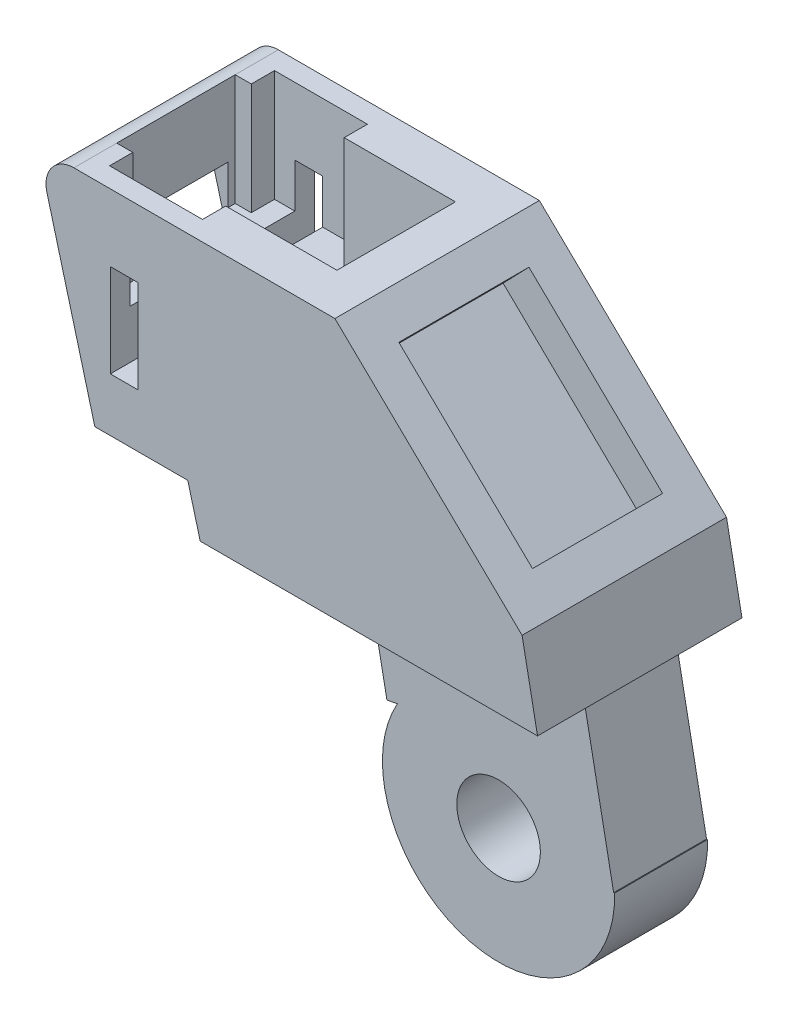
SolidWorks part; units mm, degrees
ref_plane "Front Plane" through (0, 0, 0) normal (0, 0, 1) x (1, 0, 0)
ref_plane "Top Plane" through (0, 0, 0) normal (0, 1, 0) x (1, 0, 0)
ref_plane "Right Plane" through (0, 0, 0) normal (1, 0, 0) x (0, 0, -1)
sketch "Sketch1" plane through (0, 0, 0) normal (0, 0, 1) x (1, 0, 0)
  line L0 (-2.3592, -1.1297) -> (-2.3592, 7.8703) construction
  line L1 (-14.5206, 6.2601) -> (9.8021, 0.4806) construction
  circle A0 centre (-2.3592, 3.3703) radius 4.5
  circle A1 centre (-2.3592, 3.3703) radius 12.5
  point P7 (-2.3592, 3.3703)
extrude "Boss-Extrude1" add sketch "Sketch1" along normal blind 10
ref_plane "Plane1" through (0, 0, 5) normal (0, 0, 1) x (1, 0, 0)
sketch "Sketch2" plane through (0, 0, 5) normal (0, 0, 1) x (1, 0, 0)
  line L0 (-16.4666, 20.0519) -> (-14.3751, 9.2918)
  line L1 (-14.3751, 9.2918) -> (-13.0259, 9.554)
  line L2 (10.0753, 5.1841) -> (10.6563, 5.5332)
  line L3 (10.6563, 5.5332) -> (6.1723, 28.6014)
  line L4 (6.1723, 28.6014) -> (-13.9692, 48.0519)
  line L5 (-13.9692, 48.0519) -> (-42.0595, 48.0519)
  line L6 (-44.9573, 44.2754) -> (-39.8064, 25.0519)
  line L7 (-39.8064, 25.0519) -> (-29.8064, 25.0519)
  line L8 (-29.8064, 25.0519) -> (-28.4666, 20.0519)
  line L9 (-28.4666, 20.0519) -> (-16.4666, 20.0519)
  arc A0 (-13.0259, 9.554) -> (10.0753, 5.1841) centre (-2.507, 1.9152) cw
  arc A1 (-42.0595, 48.0519) -> (-44.9573, 44.2754) centre (-42.0595, 45.0519) ccw
extrude "Boss-Extrude2" add sketch "Sketch2" along normal blind 11 and the other way blind 11
sketch "Sketch7" plane through (-30.877, -8.2734, 0) normal (-0.9659, -0.2588, 0) x (0, 0, 1)
  line L0 (5, 54.4025) -> (5, 34.5008) construction
  line L1 (-6, 54.4025) -> (16, 54.4025) construction
  line L2 (-6, 34.5008) -> (16, 34.5008) construction
  line L3 (-6, 44.4517) -> (16, 44.4517) construction
  line L4 (-6, 54.4025) -> (-6, 34.5008) construction
  line L5 (16, 54.4025) -> (16, 34.5008) construction
  line L6 (10.5665, 49.8097) -> (-0.5665, 49.8097)
  line L7 (10.5665, 49.8097) -> (10.5665, 39.0936)
  line L8 (10.5665, 39.0936) -> (-0.5665, 39.0936)
  line L9 (-0.5665, 49.8097) -> (-0.5665, 39.0936)
  line L10 (10.5665, 49.8097) -> (-0.5665, 39.0936) construction
  line L11 (10.5665, 39.0936) -> (-0.5665, 49.8097) construction
  point P16 (5, 44.4517)
extrude "Cut-Extrude1" cut sketch "Sketch7" against normal blind 24
sketch "Sketch8" plane through (0, 48.0519, 0) normal (0, 1, 0) x (1, 0, 0)
  line L0 (-42.0595, -5) -> (-13.9692, -5) construction
  line L1 (-42.0595, 6) -> (-42.0595, -16) construction
  line L2 (-13.9692, 6) -> (-13.9692, -16) construction
  line L7 (-42.0595, 1.3568) -> (-42.0595, -11.3932)
  line L8 (-42.0595, -11.3932) -> (-40.3295, -11.3932)
  line L13 (-40.3295, -11.3932) -> (-40.3295, -13.8932)
  line L14 (-40.3295, -13.8932) -> (-30.3295, -13.8932)
  line L15 (-30.3295, -13.8932) -> (-30.3295, -11.3932)
  line L16 (-30.3295, -11.3932) -> (-18.3595, -11.3932)
  line L17 (-18.3595, -11.3932) -> (-18.3595, 1.3568)
  line L18 (-18.3595, 1.3568) -> (-30.3295, 1.3568)
  line L19 (-30.3295, 1.3568) -> (-30.3295, 3.8568)
  line L20 (-30.3295, 3.8568) -> (-40.3295, 3.8568)
  line L21 (-40.3295, 3.8568) -> (-40.3295, 1.3568)
  line L22 (-40.3295, 1.3568) -> (-42.0595, 1.3568)
extrude "Cut-Extrude2" cut sketch "Sketch8" against normal blind 12
sketch "Sketch9" plane through (17.2704, 17.884, 0) normal (0.6947, 0.7193, 0) x (0.7193, -0.6947, 0)
  line L0 (-29.4283, 6) -> (-29.4283, -16) construction
  line L1 (-15.4283, 6) -> (-43.4283, 6) construction
  line L2 (-15.4283, -16) -> (-43.4283, -16) construction
  line L3 (-43.4283, -5) -> (-15.4283, -5) construction
  line L4 (-43.4283, 6) -> (-43.4283, -16) construction
  line L5 (-15.4283, 6) -> (-15.4283, -16) construction
  line L7 (-39.4283, -12) -> (-19.4283, -12)
  line L8 (-39.4283, -12) -> (-39.4283, 2)
  line L9 (-39.4283, 2) -> (-19.4283, 2)
  line L10 (-19.4283, -12) -> (-19.4283, 2)
  line L11 (-39.4283, -12) -> (-19.4283, 2) construction
  line L12 (-39.4283, 2) -> (-19.4283, -12) construction
  point P12 (-29.4283, -5)
  dimension "D1" = 20
  dimension "D2" = 14
extrude "Cut-Extrude3" cut sketch "Sketch9" against normal blind 4
sketch "Sketch11" plane through (0, 0, 16) normal (0, 0, 1) x (1, 0, 0)
  line L0 (-35.1419, 40.806) -> (-38.1419, 40.806)
  line L1 (-35.1419, 40.806) -> (-35.1419, 30.806)
  line L2 (-35.1419, 30.806) -> (-38.1419, 30.806)
  line L3 (-38.1419, 40.806) -> (-38.1419, 30.806)
  line L4 (-35.1419, 40.806) -> (-38.1419, 30.806) construction
  line L5 (-35.1419, 30.806) -> (-38.1419, 40.806) construction
  line L6 (-36.6419, 25.0519) -> (-36.6419, 30.806) construction
  line L7 (-39.8064, 25.0519) -> (-29.8064, 25.0519) construction
  point P4 (-36.6419, 35.806)
  dimension "D1" = 3
  dimension "D2" = 10
extrude "Cut-Extrude6" cut sketch "Sketch11" against normal blind 29
sketch "Sketch12" plane through (0, 0, -6) normal (0, 0, -1) x (-1, 0, 0)
  line L13 (-11.6158, 5.7782) -> (-10.0496, 4.8772)
  line L14 (-8.8415, 20.0506) -> (-11.6158, 5.7782)
  line L15 (17.0149, 20.0506) -> (-8.8415, 20.0506)
  line L16 (14.903, 9.1859) -> (17.0149, 20.0506)
  line L17 (13.0155, 9.5528) -> (14.903, 9.1859)
  arc A2 (13.0155, 9.5528) -> (-10.0496, 4.8772) centre (3.1792, -1.153) ccw
  arc A3 (-9.9082, 5.7705) -> (13.2469, 9.5111) centre (2.3592, 3.3703) ccw construction
extrude "Cut-Extrude7" cut sketch "Sketch12" against normal blind 6
sketch "Sketch13" plane through (0, 0, 16) normal (0, 0, 1) x (1, 0, 0)
  line L0 (-13.0259, 9.554) -> (-14.3751, 9.2918)
  line L1 (-14.3751, 9.2918) -> (-16.4666, 20.0519)
  line L2 (-16.4666, 20.0519) -> (7.8341, 20.0519)
  line L3 (10.6563, 5.5332) -> (6.1723, 28.6014) construction
  line L4 (7.8341, 20.0519) -> (10.6563, 5.5332)
  line L5 (10.6563, 5.5332) -> (10.0753, 5.1841)
  arc A0 (-13.0259, 9.554) -> (10.0753, 5.1841) centre (-3.0653, -1.0361) cw
extrude "Cut-Extrude8" cut sketch "Sketch13" against normal blind 6
sketch "Sketch14" plane through (11.3047, 2.1974, 0) normal (0.9816, 0.1908, 0) x (0, 0, -1)
  line L0 (0, -8.7414) -> (0, 11.8639) construction
  line L5 (-10, 18.1886) -> (0, 18.1886)
  line L6 (-10, 18.1886) -> (-10, 1.5613)
  line L7 (-10, 1.5613) -> (0, 1.5613)
  line L8 (0, 18.1886) -> (0, 1.5613)
  line L9 (-10, 18.1886) -> (0, 1.5613) construction
  line L10 (-10, 1.5613) -> (0, 18.1886) construction
  point P4 (-5, 9.8749)
extrude "Cut-Extrude11" cut sketch "Sketch14" against normal blind 1
